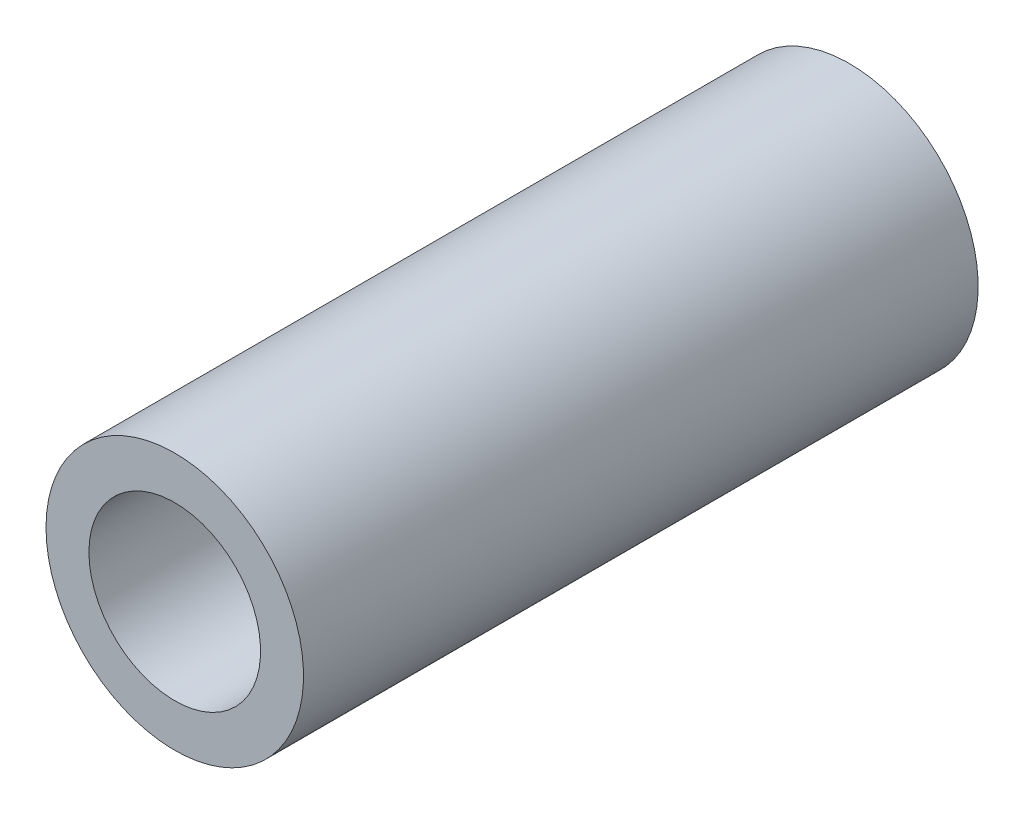
SolidWorks part; units mm, degrees
ref_plane "Front Plane" through (0, 0, 0) normal (0, 0, 1) x (1, 0, 0)
ref_plane "Top Plane" through (0, 0, 0) normal (0, 1, 0) x (1, 0, 0)
ref_plane "Right Plane" through (0, 0, 0) normal (1, 0, 0) x (0, 0, -1)
sketch "Sketch1" plane through (0, 0, 0) normal (0, 0, 1) x (1, 0, 0)
  circle A0 centre (0, 0) radius 2.3813
  circle A1 centre (0, 0) radius 1.5875
  dimension "D1" = 4.7625
  dimension "D2" = 3.175
extrude "Boss-Extrude1" add sketch "Sketch1" along normal blind 12.4778
